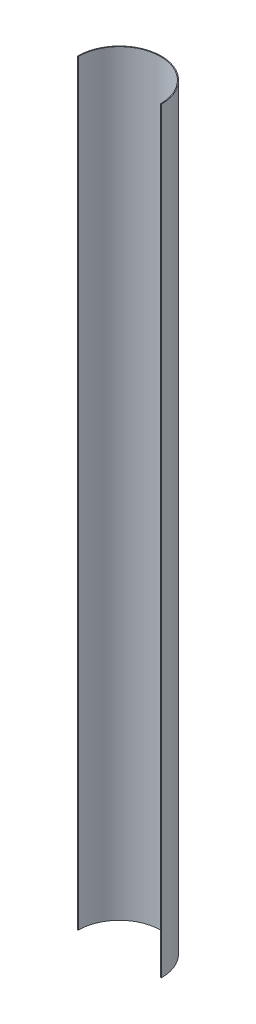
SolidWorks part; units mm, degrees
material "Thornel Mat VMA"
ref_plane "Plan de face" through (0, 0, 0) normal (0, 0, 1) x (1, 0, 0)
ref_plane "Plan de dessus" through (0, 0, 0) normal (0, 1, 0) x (1, 0, 0)
ref_plane "Plan de droite" through (0, 0, 0) normal (1, 0, 0) x (0, 0, -1)
sketch "Esquisse1" plane through (0, 0, 0) normal (0, 1, 0) x (1, 0, 0)
  circle A0 centre (0, 0) radius 77.5
  circle A1 centre (0, 0) radius 76
  dimension "D1" = 155
  dimension "D2" = 152
extrude "Boss.-Extru.1" add sketch "Esquisse1" along normal blind 1400
sketch "Esquisse2" plane through (0, 0, 0) normal (0, -1, 0) x (1, 0, 0)
  line L1 (105.5637, 0) -> (-116.3844, 0)
  line L2 (105.5637, 0) -> (105.5637, 120.7277)
  line L3 (105.5637, 120.7277) -> (-116.3844, 120.7277)
  line L4 (-116.3844, 0) -> (-116.3844, 120.7277)
extrude "Enlèv. mat.-Extru.1" cut sketch "Esquisse2" against normal blind 1400
